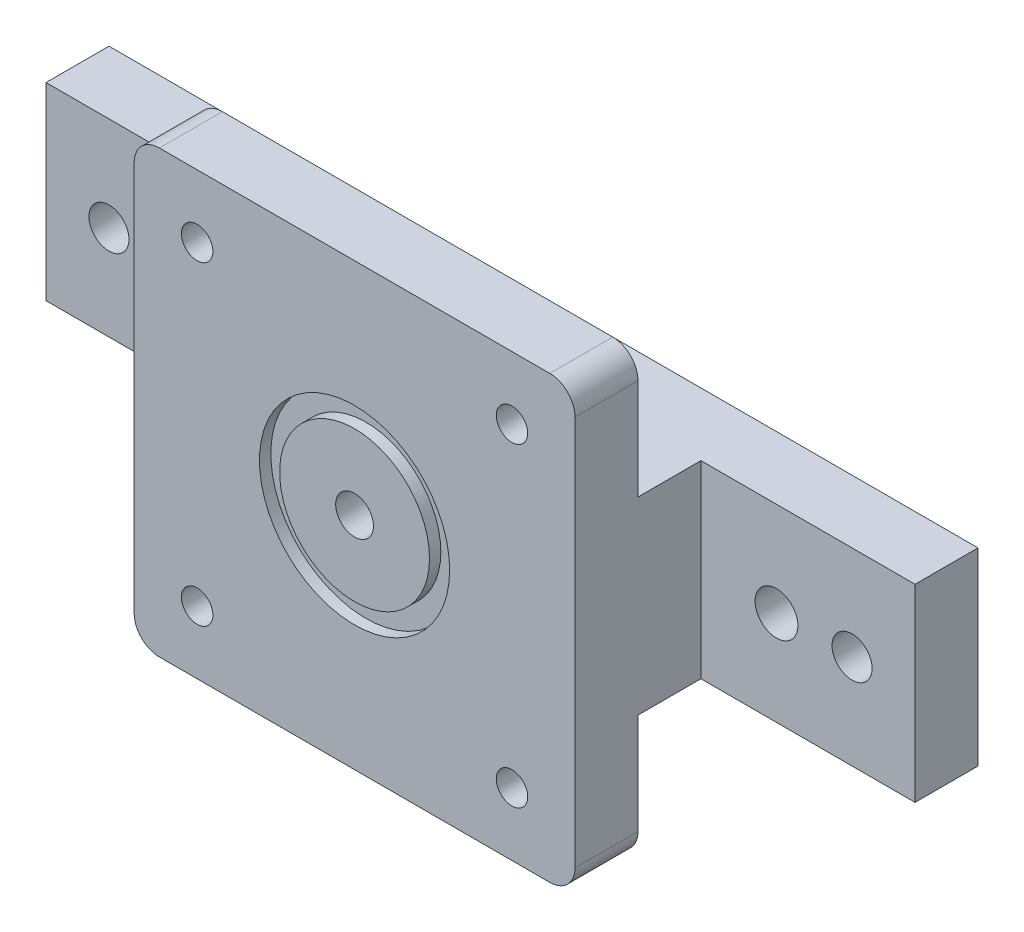
SolidWorks part; units mm, degrees
material "6061-T6 (SS)"
ref_plane "Front Plane" through (0, 0, 0) normal (0, 0, 1) x (1, 0, 0)
ref_plane "Top Plane" through (0, 0, 0) normal (0, 1, 0) x (1, 0, 0)
ref_plane "Right Plane" through (0, 0, 0) normal (1, 0, 0) x (0, 0, -1)
sketch "Sketch1" plane through (0, 0, 0) normal (0, 0, 1) x (1, 0, 0)
  line L1 (0, 0) -> (60, 0)
  line L2 (0, 0) -> (0, 20)
  line L3 (0, 20) -> (60, 20)
  line L4 (60, 0) -> (60, 20)
  dimension "D1" = 60
  dimension "D2" = 20
extrude "Boss-Extrude1" add sketch "Sketch1" along normal blind 37
sketch "Sketch2" plane through (0, 0, 37) normal (0, 0, 1) x (1, 0, 0)
  line L0 (60, 0) -> (60, 20) construction
  line L1 (60, 20) -> (0, 20) construction
  point P0 (32.15, 17.95)
  dimension "D1" = 27.85
  dimension "D2" = 2.05
ref_plane "Plane1" through (0, 12.5, 0) normal (0, 1, 0) x (1, 0, 0)
sketch "Sketch7" plane through (0, 0, 0) normal (0, 0, -1) x (-1, 0, 0)
  line L0 (-60, 0) -> (-60, 20) construction
  line L1 (0, 0) -> (-60, 0)
  line L2 (0, 0) -> (0, 5)
  line L3 (0, 5) -> (-60, 5)
  line L4 (-60, 0) -> (-60, 5)
  dimension "D1" = 5
extrude "Cut-Extrude2" cut sketch "Sketch7" against normal through all both contours L4 L3 L2 L1
ref_plane "Plane2" through (0, 0, 32) normal (0, 0, 1) x (1, 0, 0)
sketch "Sketch15" plane through (0, 20, 0) normal (0, 1, 0) x (1, 0, 0)
  line L0 (60, 0) -> (0, 0) construction
  line L1 (60, -37) -> (60, 0) construction
  circle A0 centre (22.381, -23.279) radius 2.5
  circle A1 centre (22.381, -3.721) radius 2.5
  circle A2 centre (41.939, -3.721) radius 2.5
  circle A3 centre (41.939, -23.279) radius 2.5
  dimension "D1" = 5
  dimension "D2" = 5
  dimension "D3" = 5
  dimension "D4" = 5
  dimension "D6" = 19.558
  dimension "D7" = 19.558
  dimension "D8" = 19.558
  dimension "D9" = 3.721
  dimension "D10" = 18.061
  dimension "D5" = 19.558
sketch "Sketch16" plane through (0, 20, 0) normal (0, 1, 0) x (1, 0, 0)
  line L1 (60, -37) -> (60, 0) construction
  line L3 (60, 0) -> (0, 0) construction
  circle A0 centre (34.7475, -4.83) radius 1.75
  dimension "D1" = 3.5
  dimension "D2" = 25.2525
  dimension "D3" = 4.83
extrude "Boss-Extrude3" add sketch "Sketch16" along normal blind 1.85
sketch "Sketch19" plane through (0, 21.85, 0) normal (0, 1, 0) x (1, 0, 0)
  point P0 (34.7475, -4.83)
sketch "Sketch27" plane through (0, 20, 0) normal (0, 1, 0) x (1, 0, 0)
  line L0 (60, 0) -> (0, 0) construction
  line L1 (60, -37) -> (59.66, -37)
  line L2 (60, -37) -> (60, 0)
  line L3 (60, 0) -> (59.66, 0)
  line L4 (59.66, -37) -> (59.66, 0)
  line L5 (60, -37) -> (0, -37) construction
  line L6 (0, 0) -> (4.66, 0)
  line L7 (0, 0) -> (0, -37)
  line L8 (0, -37) -> (4.66, -37)
  line L9 (4.66, 0) -> (4.66, -37)
  dimension "D1" = 4.66
  dimension "D2" = 0.34
extrude "Cut-Extrude9" cut sketch "Sketch27" against normal through all
sketch "Sketch28" plane through (0, 20, 0) normal (0, 1, 0) x (1, 0, 0)
  line L0 (59.66, 0) -> (4.66, 0) construction
  line L1 (59.66, -37) -> (51.21, -37)
  line L2 (59.66, -37) -> (59.66, -5)
  line L3 (59.66, -5) -> (51.21, -5)
  line L4 (51.21, -37) -> (51.21, -5)
  line L5 (4.66, -37) -> (13.11, -37)
  line L6 (4.66, -37) -> (4.66, -5)
  line L7 (4.66, -5) -> (13.11, -5)
  line L8 (13.11, -37) -> (13.11, -5)
  dimension "D1" = 8.45
  dimension "D2" = 8.45
  dimension "D3" = 5
  dimension "D4" = 5
extrude "Cut-Extrude10" cut sketch "Sketch28" against normal through all
sketch "Sketch29" plane through (0, 0, 5) normal (0, 0, 1) x (1, 0, 0)
  line L0 (13.11, 20) -> (4.66, 20) construction
  line L1 (4.66, 5) -> (4.66, 20) construction
  line L2 (59.66, 20) -> (51.21, 20) construction
  line L3 (59.66, 5) -> (59.66, 20) construction
  circle A0 centre (8.66, 13) radius 1.5
  circle A1 centre (55.66, 13) radius 1.5
  dimension "D1" = 7
  dimension "D2" = 4
  dimension "D3" = 7
  dimension "D4" = 4
  dimension "D5" = 3
  dimension "D6" = 3
sketch "Sketch32" plane through (0, 5, 0) normal (0, -1, 0) x (1, 0, 0)
  line L0 (13.11, 37) -> (51.21, 37) construction
  line L1 (51.21, 5) -> (51.21, 37) construction
  line L2 (13.11, 37) -> (13.11, 5) construction
  circle A0 centre (23.61, 33.5) radius 1
  circle A1 centre (40.71, 33.5) radius 1
  dimension "D1" = 2
  dimension "D2" = 2
  dimension "D3" = 3.5
  dimension "D4" = 10.5
  dimension "D5" = 3.5
  dimension "D6" = 10.5
sketch "Sketch35" plane through (0, 20, 0) normal (0, 1, 0) x (1, 0, 0)
  line L0 (51.21, -5) -> (51.21, -37) construction
  line L1 (13.11, -37) -> (51.21, -37)
  line L2 (13.11, -37) -> (13.11, -17)
  line L3 (13.11, -17) -> (51.21, -17)
  line L4 (51.21, -37) -> (51.21, -17)
  line L5 (59.66, 0) -> (4.66, 0) construction
  dimension "D1" = 17
extrude "Cut-Extrude13" cut sketch "Sketch35" against normal through all both and the other way through all flip side to cut
sketch "Sketch39" plane through (0, 20, 0) normal (0, 1, 0) x (1, 0, 0)
  line L0 (13.11, -17) -> (51.21, -17) construction
  line L1 (13.11, -37) -> (20.11, -37)
  line L2 (13.11, -37) -> (13.11, -27)
  line L3 (13.11, -27) -> (20.11, -27)
  line L4 (20.11, -37) -> (20.11, -27)
  line L5 (51.21, -37) -> (44.21, -37)
  line L6 (51.21, -37) -> (51.21, -27)
  line L7 (51.21, -27) -> (44.21, -27)
  line L8 (44.21, -37) -> (44.21, -27)
  dimension "D1" = 7
  dimension "D2" = 7
  dimension "D3" = 10
  dimension "D4" = 10
extrude "Cut-Extrude14" cut sketch "Sketch39" against normal through all both
sketch "Sketch40" plane through (0, 0, 27) normal (0, 0, 1) x (1, 0, 0)
  line L0 (13.11, 5) -> (13.11, 20) construction
  line L1 (51.21, 5) -> (51.21, 20) construction
  line L4 (20.11, 20) -> (13.11, 20) construction
  line L5 (51.21, 20) -> (44.21, 20) construction
  circle A0 centre (17.11, 12.5) radius 1
  circle A1 centre (47.21, 12.5) radius 1
  dimension "D1" = 2
  dimension "D2" = 2
  dimension "D3" = 4
  dimension "D4" = 4
  dimension "D5" = 7.5
  dimension "D6" = 7.5
hole_wizard "M3 Clearance Hole2" positions "Sketch41" profile "Sketch42" hole size "M3" standard "ANSI Metric" end condition through all
sketch "Sketch41" plane through (0, 0, 27) normal (0, 0, 1) x (1, 0, 0)
  point P0 (17.11, 12.5)
  point P3 (47.21, 12.5)
sketch "Sketch42" plane through (17.11, 12.5, 27) normal (1, 0, 0) x (0, -1, 0)
  line L0 (0, 0) -> (0, 10)
  line L1 (0, 10) -> (1.7, 10)
  line L2 (1.7, 10) -> (1.7, 0)
  line L5 (1.7, 0) -> (0, 0)
  line L11 (0, -6.35) -> (0, 107.95) construction
  dimension "Thru Hole Dia." = 3.4
  dimension "Thru Hole Depth" = 10
hole_wizard "Tap Drill for #10-32 Tap1" positions "Sketch3" profile "Sketch4" hole size "#10-32" standard "ANSI Inch"
sketch "Sketch3" plane through (0, 0, 37) normal (0, 0, 1) x (1, 0, 0)
  line L1 (44.21, 20) -> (20.11, 20) construction
  line L3 (51.21, 5) -> (51.21, 20) construction
  point P0 (32.16, 12.5)
  dimension "D1" = 7.5
  dimension "D2" = 19.05
sketch "Sketch4" plane through (32.16, 12.5, 37) normal (1, 0, 0) x (0, -1, 0)
  line L0 (0, 0) -> (0, 6.2133)
  line L1 (0, 6.2133) -> (2.0193, 5)
  line L2 (2.0193, 5) -> (2.0193, 0)
  line L5 (2.0193, 0) -> (0, 0)
  line L10 (0, 6.2133) -> (-2.0193, 5) construction
  line L11 (0, -6.35) -> (0, 107.95) construction
  dimension "Hole Dia." = 4.0386
  dimension "Hole Depth" = 5
  dimension "Drill Angle" = 118
sketch "Sketch6" plane through (0, 0, 17) normal (0, 0, -1) x (-1, 0, 0)
  line L1 (-51.21, 5) -> (-51.21, 20) construction
  line L6 (-13.11, 20) -> (-51.21, 20) construction
  circle A2 centre (-32.16, 12.5) radius 0.625
  point P5 (-32.155, 12.5)
  dimension "D1" = 1.25
  dimension "D2" = 7.5
  dimension "D3" = 19.05
extrude "Cut-Extrude1" cut sketch "Sketch6" against normal blind 27
ref_plane "Plane3" through (0, 12.5, 0) normal (0, 1, 0) x (1, 0, 0)
sketch "Sketch44" plane through (0, 12.5, 0) normal (0, 1, 0) x (1, 0, 0)
  line L0 (32.16, -37) -> (32.16, -29.45)
  line L1 (44.21, -37) -> (20.11, -37) construction
  line L2 (32.16, -29.45) -> (32.16, -17)
  line L3 (32.16, -29.45) -> (32.78, -29.45)
  line L4 (32.78, -29.45) -> (34.18, -30.29)
  line L5 (34.18, -30.29) -> (34.18, -37)
  line L6 (34.18, -37) -> (32.16, -37)
  line L8 (44.21, -27) -> (44.21, -37) construction
  line L10 (32.16, -17) -> (32.78, -17)
  line L11 (13.11, -17) -> (51.21, -17) construction
  line L12 (32.78, -17) -> (32.78, -29.45)
  dimension "D1" = 12.05
  dimension "D2" = 6.71
  dimension "D3" = 0.62
  dimension "D4" = 2.02
  dimension "D5" = 1.4
  dimension "D6" = 0.84
  dimension "D7" = 0
  dimension "D8" = 0.62
revolve "Cut-Revolve1" cut sketch "Sketch44" angle 360 about L0
sketch "Sketch48" plane through (0, 0, 17) normal (0, 0, -1) x (-1, 0, 0)
  line L0 (-13.11, 20) -> (-51.21, 20) construction
  line L1 (-13.11, 5) -> (-13.11, 20) construction
  line L2 (-51.21, 5) -> (-51.21, 20) construction
  circle A0 centre (-37.21, 15) radius 1.58
  circle A1 centre (-27.11, 15) radius 1.58
  dimension "D1" = 3.16
  dimension "D2" = 3.16
  dimension "D3" = 5
  dimension "D4" = 5
  dimension "D5" = 14
  dimension "D6" = 14
extrude "Cut-Extrude17" cut sketch "Sketch48" against normal blind 8
sketch "Sketch49" plane through (0, 0, 17) normal (0, 0, -1) x (-1, 0, 0)
  circle A0 centre (-47.21, 12.5) radius 1.7092
  circle A1 centre (-17.11, 12.5) radius 1.7
  circle A2 centre (-27.11, 15) radius 1.58
  circle A3 centre (-37.21, 15) radius 1.58
extrude "Boss-Extrude4" add sketch "Sketch49" against normal blind 10
sketch "Sketch50" plane through (0, 0, 17) normal (0, 0, -1) x (-1, 0, 0)
  line L1 (-51.21, 20) -> (-13.11, 20)
  line L2 (-51.21, 20) -> (-51.21, 5)
  line L3 (-51.21, 5) -> (-13.11, 5)
  line L4 (-13.11, 20) -> (-13.11, 5)
  circle A0 centre (-32.16, 12.5) radius 0.625
extrude "Boss-Extrude5" add sketch "Sketch50" along normal blind 17
sketch "Sketch53" plane through (0, 0, 0) normal (0, 0, -1) x (-1, 0, 0)
  line L1 (-13.11, 5) -> (2.34, 5)
  line L2 (-13.11, 5) -> (-13.11, 20)
  line L3 (-13.11, 20) -> (2.34, 20)
  line L4 (2.34, 5) -> (2.34, 20)
  line L5 (-51.21, 5) -> (-66.66, 5)
  line L6 (-51.21, 5) -> (-51.21, 20)
  line L7 (-51.21, 20) -> (-66.66, 20)
  line L8 (-66.66, 5) -> (-66.66, 20)
  dimension "D1" = 15.45
  dimension "D2" = 15
  dimension "D3" = 15.45
  dimension "D4" = 15
extrude "Boss-Extrude6" add sketch "Sketch53" against normal blind 5
sketch "Sketch54" plane through (0, 20, 0) normal (0, 1, 0) x (1, 0, 0)
  line L2 (51.21, -5) -> (51.21, -27) construction
  line L3 (-2.34, 0) -> (66.66, 0) construction
  circle A0 centre (34.7475, -4.83) radius 1.75
  dimension "D1" = 16.4625
  dimension "D2" = 4.83
  dimension "D3" = 3.5
extrude "Boss-Extrude7" add sketch "Sketch54" along normal blind 1.85
hole_wizard "Tap Drill for M2.5x0.45 Tap2" positions "Sketch20" profile "Sketch21" hole size "M2.5x0.45" standard "ANSI Metric"
sketch "Sketch20" plane through (0, 21.85, 0) normal (0, 1, 0) x (1, 0, 0)
  point P0 (34.7475, -4.83)
sketch "Sketch21" plane through (34.7475, 21.85, 4.83) normal (1, 0, 0) x (0, 0, 1)
  line L0 (0, 0) -> (0, 4.6159)
  line L1 (0, 4.6159) -> (1.025, 4)
  line L2 (1.025, 4) -> (1.025, 0.025)
  line L3 (1.025, 0.025) -> (1.05, 0)
  line L5 (1.05, 0) -> (0, 0)
  line L6 (-1.025, 0.025) -> (-1.05, 0) construction
  line L10 (0, 4.6159) -> (-1.025, 4) construction
  line L11 (0, -6.35) -> (0, 107.95) construction
  dimension "Hole Dia." = 2.05
  dimension "Hole Depth" = 4
  dimension "Near C'Sink Dia." = 2.1
  dimension "Near C'Sink Angle" = 90
  dimension "Drill Angle" = 118
hole_wizard "M3 Clearance Hole1" positions "Sketch30" profile "Sketch31" hole size "M3" standard "ANSI Metric" end condition through all
sketch "Sketch30" plane through (0, 0, 0) normal (0, 0, 1) x (1, 0, 0)
  line L0 (-2.34, 20) -> (13.11, 20) construction
  line L1 (51.21, 20) -> (66.66, 20) construction
  line L2 (66.66, 20) -> (66.66, 5) construction
  line L3 (-2.34, 5) -> (-2.34, 20) construction
  point P0 (8.66, 12.5)
  point P3 (55.66, 12.5)
  dimension "D1" = 7.5
  dimension "D2" = 7.5
  dimension "D3" = 11
  dimension "D4" = 11
sketch "Sketch31" plane through (8.66, 12.5, 0) normal (1, 0, 0) x (0, 1, 0)
  line L0 (0, 0) -> (0, 37)
  line L1 (0, 37) -> (1.7, 37)
  line L2 (1.7, 37) -> (1.7, 0)
  line L5 (1.7, 0) -> (0, 0)
  line L11 (0, -6.35) -> (0, 107.95) construction
  dimension "Thru Hole Dia." = 3.4
  dimension "Thru Hole Depth" = 37
sketch "Sketch56" plane through (0, 0, 0) normal (0, 0, -1) x (-1, 0, 0)
  line L0 (2.34, 5) -> (2.34, 20) construction
  line L1 (2.34, 20) -> (-66.66, 20) construction
  line L2 (-66.66, 20) -> (-66.66, 5) construction
  circle A0 centre (-61.66, 12.5) radius 1.59
  circle A1 centre (-2.66, 12.5) radius 1.59
  dimension "D1" = 3.18
  dimension "D2" = 3.18
  dimension "D3" = 5
  dimension "D4" = 7.5
  dimension "D5" = 5
  dimension "D6" = 7.5
extrude "Cut-Extrude21" cut sketch "Sketch56" against normal blind 5
sketch "Sketch57" plane through (0, 0, 0) normal (0, 0, -1) x (-1, 0, 0)
  line L1 (-38.66, 15) -> (-25.66, 15)
  line L2 (-38.66, 15) -> (-38.66, 10)
  line L3 (-38.66, 10) -> (-25.66, 10)
  line L4 (-25.66, 15) -> (-25.66, 10)
  circle A0 centre (-32.16, 12.5) radius 0.625 construction
  dimension "D4" = 2.5
  dimension "D1" = 5
  dimension "D2" = 13
  dimension "D3" = 6.5
extrude "Cut-Extrude22" cut sketch "Sketch57" against normal blind 0.8
fillet "Fillet1" radius 0.79 4 edges at (25.66, 10, 0.4) (25.66, 15, 0.4) (38.66, 15, 0.4) (38.66, 10, 0.4)
sketch "Sketch58" plane through (0, 20, 0) normal (0, 1, 0) x (1, 0, 0)
  line L1 (20.11, -27) -> (13.11, -27)
  line L2 (20.11, -27) -> (20.11, -37)
  line L3 (20.11, -37) -> (13.11, -37)
  line L4 (13.11, -27) -> (13.11, -37)
  line L5 (44.21, -27) -> (51.21, -27)
  line L6 (44.21, -27) -> (44.21, -37)
  line L7 (44.21, -37) -> (51.21, -37)
  line L8 (51.21, -27) -> (51.21, -37)
  dimension "D1" = 7
  dimension "D2" = 7
extrude "Boss-Extrude8" add sketch "Sketch58" against normal up to surface (15 mm away) up to face at (32.16, 5, 16.8333)
hole_wizard "Tap Drill for M3x0.5 Tap1" positions "Sketch33" profile "Sketch34" hole size "M3x0.5" standard "ANSI Metric" end condition through all
sketch "Sketch33" plane through (0, 5, 0) normal (0, -1, 0) x (-1, 0, 0)
  line L0 (-13.11, -37) -> (-51.21, -37) construction
  line L1 (-13.11, -37) -> (-13.11, -5) construction
  line L2 (-51.21, -5) -> (-51.21, -37) construction
  point P0 (-16.61, -33.5)
  point P3 (-47.71, -33.5)
  dimension "D1" = 3.5
  dimension "D2" = 3.5
  dimension "D3" = 3.5
  dimension "D4" = 3.5
sketch "Sketch34" plane through (16.61, 5, 33.5) normal (1, 0, 0) x (0, 0, -1)
  line L0 (0, 0) -> (0, 16.85)
  line L1 (0, 16.85) -> (1.25, 16.85)
  line L2 (1.25, 16.85) -> (1.25, 0)
  line L5 (1.25, 0) -> (0, 0)
  line L11 (0, -6.35) -> (0, 107.95) construction
  dimension "Thru Hole Dia." = 2.5
  dimension "Thru Hole Depth" = 16.85
sketch "Sketch59" plane through (0, 20, 0) normal (0, 1, 0) x (1, 0, 0)
  line L0 (13.11, -37) -> (13.11, -5) construction
  line L1 (51.21, -37) -> (13.11, -37)
  line L2 (51.21, -37) -> (51.21, -15)
  line L3 (51.21, -15) -> (13.11, -15)
  line L4 (13.11, -37) -> (13.11, -15)
  dimension "D1" = 22
extrude "Cut-Extrude23" cut sketch "Sketch59" against normal through all
hole_wizard "Ø3.0mm Dowel Hole1" positions "Sketch62" profile "Sketch63" hole size "Ø3.0" standard "ANSI Metric"
sketch "Sketch62" plane through (0, 0, 15) normal (0, 0, 1) x (1, 0, 0)
  point P0 (32.16, 12.5)
sketch "Sketch63" plane through (32.16, 12.5, 15) normal (1, 0, 0) x (0, -1, 0)
  line L0 (0, 0) -> (0, 5.9013)
  line L1 (0, 5.9013) -> (1.5, 5)
  line L2 (1.5, 5) -> (1.5, 0)
  line L5 (1.5, 0) -> (0, 0)
  line L10 (0, 5.9013) -> (-1.5, 5) construction
  line L11 (0, -6.35) -> (0, 107.95) construction
  dimension "Hole Dia." = 3
  dimension "Hole Depth" = 5
  dimension "Drill Angle" = 118
sketch "Sketch65" plane through (0, 0, 15) normal (0, 0, 1) x (1, 0, 0)
  line L1 (14.66, 30) -> (49.66, 30)
  line L2 (14.66, 30) -> (14.66, -5)
  line L3 (14.66, -5) -> (49.66, -5)
  line L4 (49.66, 30) -> (49.66, -5)
  circle A0 centre (32.16, 12.5) radius 0.625 construction
  circle A1 centre (19.66, 25) radius 1
  circle A2 centre (44.66, 25) radius 1
  circle A3 centre (44.66, 0) radius 1
  circle A4 centre (19.66, 0) radius 1
  circle A5 centre (32.16, 12.5) radius 4
  dimension "D4" = 17.5
  dimension "D5" = 25
  dimension "D6" = 25
  dimension "D7" = 25
  dimension "D8" = 25
  dimension "D9" = 5
  dimension "D10" = 5
  dimension "D11" = 5
  dimension "D12" = 5
  dimension "D13" = 2
  dimension "D14" = 2
  dimension "D15" = 2
  dimension "D16" = 2
  dimension "D1" = 35
  dimension "D2" = 35
  dimension "D3" = 17.5
extrude "Boss-Extrude9" add sketch "Sketch65" against normal blind 5
sketch "Sketch64" plane through (0, 0, 15) normal (0, 0, 1) x (1, 0, 0)
  circle A0 centre (32.16, 12.5) radius 5.95
  circle A1 centre (32.16, 12.5) radius 7.55
  dimension "D1" = 11.9
  dimension "D2" = 15.1
extrude "Cut-Extrude24" cut sketch "Sketch64" against normal blind 0.9
hole_wizard "Tap Drill for M3x0.5 Tap2" positions "Sketch66" profile "Sketch67" hole size "M3x0.5" standard "ANSI Metric" end condition through all
sketch "Sketch66" plane through (0, 0, 15) normal (0, 0, 1) x (1, 0, 0)
  point P0 (19.66, 0)
  point P3 (19.66, 25)
  point P6 (44.66, 25)
  point P9 (44.66, 0)
sketch "Sketch67" plane through (19.66, 0, 15) normal (1, 0, 0) x (0, -1, 0)
  line L0 (0, 0) -> (0, 15)
  line L1 (0, 15) -> (1.25, 15)
  line L2 (1.25, 15) -> (1.25, 0)
  line L5 (1.25, 0) -> (0, 0)
  line L11 (0, -6.35) -> (0, 107.95) construction
  dimension "Thru Hole Dia." = 2.5
  dimension "Thru Hole Depth" = 15
sketch "Sketch68" plane through (0, 20, 0) normal (0, 1, 0) x (1, 0, 0)
  line L0 (-2.34, -5) -> (13.11, -5) construction
  line L1 (14.66, -15) -> (13.11, -15)
  line L2 (14.66, -15) -> (14.66, -5)
  line L3 (14.66, -5) -> (13.11, -5)
  line L4 (13.11, -15) -> (13.11, -5)
  line L5 (13.11, -15) -> (13.11, -5) construction
  line L7 (49.66, -15) -> (51.21, -15)
  line L8 (49.66, -15) -> (49.66, -5)
  line L9 (49.66, -5) -> (51.21, -5)
  line L10 (51.21, -15) -> (51.21, -5)
extrude "Cut-Extrude25" cut sketch "Sketch68" against normal through all
fillet "Fillet2" radius 2 4 edges at (49.66, -5, 12.5) (14.66, -5, 12.5) (14.66, 30, 12.5) (49.66, 30, 12.5)
